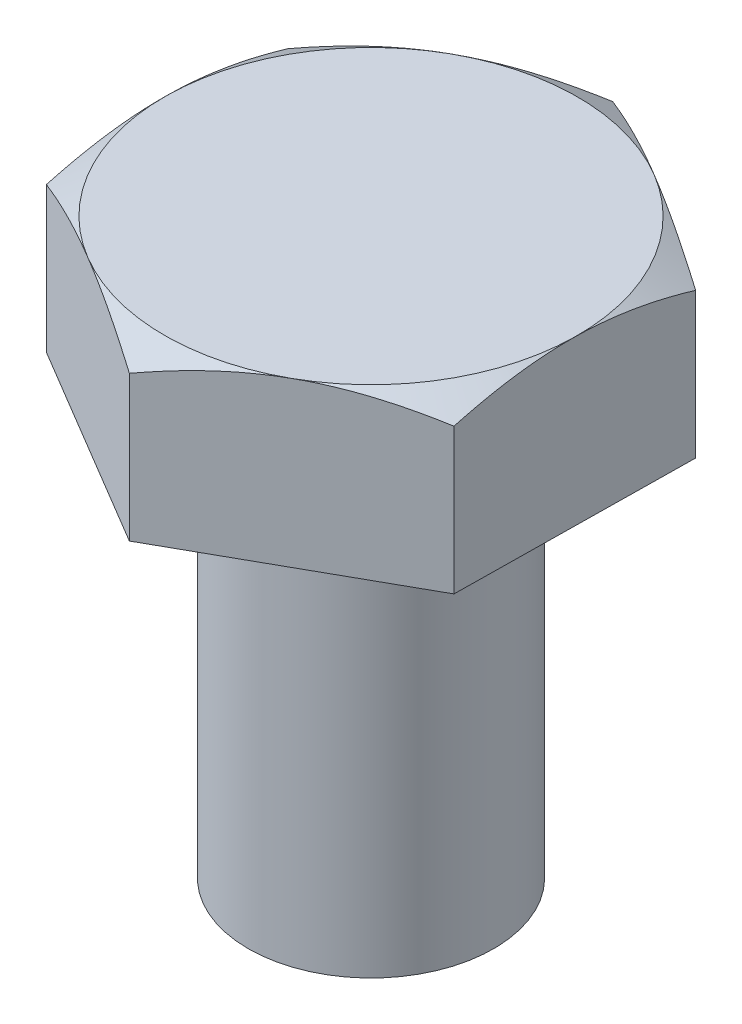
SolidWorks part; units mm, degrees
ref_plane "Front Plane" through (0, 0, 0) normal (0, 0, 1) x (1, 0, 0)
ref_plane "Top Plane" through (0, 0, 0) normal (0, 1, 0) x (1, 0, 0)
ref_plane "Right Plane" through (0, 0, 0) normal (1, 0, 0) x (0, 0, -1)
sketch "Sketch1" plane through (0, 0, 0) normal (0, 1, 0) x (1, 0, 0)
  circle A0 centre (0, 0) radius 3
extrude "Boss-Extrude1" add sketch "Sketch1" against normal blind 10
sketch "Sketch2" plane through (0, 0, 0) normal (0, 1, 0) x (1, 0, 0)
  line L1 (5.0842, 2.8465) -> (0.077, 5.8263)
  line L2 (0.077, 5.8263) -> (-5.0072, 2.9798)
  line L3 (-5.0072, 2.9798) -> (-5.0842, -2.8465)
  line L4 (-5.0842, -2.8465) -> (-0.077, -5.8263)
  line L5 (-0.077, -5.8263) -> (5.0072, -2.9798)
  line L6 (5.0072, -2.9798) -> (5.0842, 2.8465)
  circle A0 centre (0, 0) radius 5.0461 construction
extrude "Boss-Extrude2" add sketch "Sketch2" along normal blind 4 separate body
sketch "Sketch3" plane through (0, 4, 0) normal (0, 1, 0) x (1, 0, 0)
  line L1 (5.0842, 2.8465) -> (0.077, 5.8263)
  line L2 (0.077, 5.8263) -> (-5.0072, 2.9798)
  line L3 (-5.0072, 2.9798) -> (-5.0842, -2.8465)
  line L4 (-5.0842, -2.8465) -> (-0.077, -5.8263)
  line L5 (-0.077, -5.8263) -> (5.0072, -2.9798)
  line L6 (5.0072, -2.9798) -> (5.0842, 2.8465)
  circle A0 centre (0, 0) radius 5.0461
  circle A1 centre (0, 0) radius 5.0461 construction
extrude "Cut-Extrude10" cut sketch "Sketch3" against normal blind 14 draft 60 flip side to cut contours A0 L1
